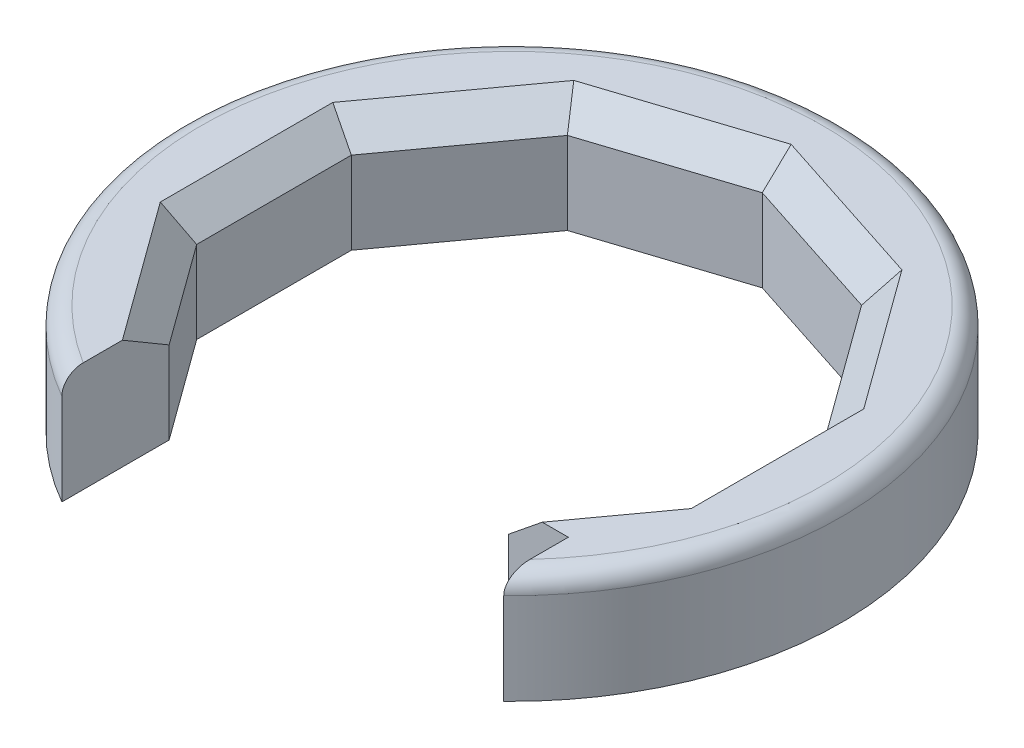
SolidWorks part; units mm, degrees
ref_plane "Front Plane" through (0, 0, 0) normal (0, 0, 1) x (1, 0, 0)
ref_plane "Top Plane" through (0, 0, 0) normal (0, 1, 0) x (1, 0, 0)
ref_plane "Right Plane" through (0, 0, 0) normal (1, 0, 0) x (0, 0, -1)
sketch "Sketch1" plane through (0, 0, 0) normal (0, 1, 0) x (1, 0, 0)
  line L1 (16.0689, 22.1169) -> (0, 27.338)
  line L2 (0, 27.338) -> (-16.0689, 22.1169)
  line L3 (-16.0689, 22.1169) -> (-26, 8.4479)
  line L4 (-26, 8.4479) -> (-26, -8.4479)
  line L5 (-26, -8.4479) -> (-16.0689, -22.1169)
  line L6 (-16.0689, -22.1169) -> (0, -27.338)
  line L7 (0, -27.338) -> (16.0689, -22.1169)
  line L8 (16.0689, -22.1169) -> (26, -8.4479)
  line L9 (26, -8.4479) -> (26, 8.4479)
  line L10 (26, 8.4479) -> (16.0689, 22.1169)
  circle A0 centre (0, 0) radius 36
  circle A1 centre (0, 0) radius 26 construction
  dimension "D1" = 72
  dimension "D2" = 10
extrude "Boss-Extrude1" add sketch "Sketch1" along normal blind 12
fillet "Fillet1" radius 2 1 edges at (0, 12, 36)
chamfer "Chamfer1" distance 3 angle 45 10 edges at (-8.0344, 12, 24.7275) (8.0344, 12, 24.7275) (21.0344, 12, 15.2824) (26, 12, 0) (21.0344, 12, -15.2824) (8.0344, 12, -24.7275) (-8.0344, 12, -24.7275) (-21.0344, 12, -15.2824) (-26, 12, 0) (-21.0344, 12, 15.2824)
sketch "Sketch2" plane through (0, 0, 0) normal (0, 1, 0) x (1, 0, 0)
  line L0 (0, 0) -> (0, -61.8485) construction
  line L1 (25, -61.8485) -> (-18, -61.8485)
  line L2 (25, -61.8485) -> (25, -18.8485)
  line L3 (25, -18.8485) -> (-18, -18.8485)
  line L4 (-18, -61.8485) -> (-18, -18.8485)
  line L5 (25, -61.8485) -> (-18, -18.8485) construction
  line L6 (25, -18.8485) -> (-18, -61.8485) construction
  line L7 (0, 0) -> (3.5, -40.3485) construction
  point P0 (3.5, -40.3485)
  dimension "D1" = 7
  dimension "D2" = 40.5
  dimension "D3" = 43
  dimension "D4" = 43
extrude "Cut-Extrude2" cut sketch "Sketch2" along normal through all
